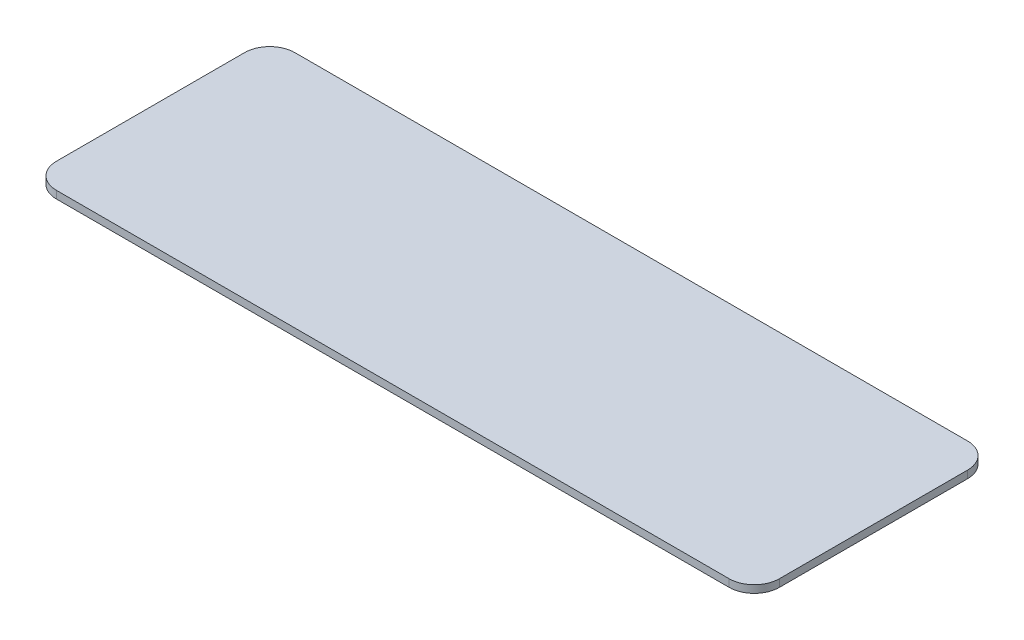
SolidWorks part; units mm, degrees
ref_plane "Front Plane" through (0, 0, 0) normal (0, 0, 1) x (1, 0, 0)
ref_plane "Top Plane" through (0, 0, 0) normal (0, 1, 0) x (1, 0, 0)
ref_plane "Right Plane" through (0, 0, 0) normal (1, 0, 0) x (0, 0, -1)
sketch "Sketch1" plane through (0, 0, 0) normal (0, 1, 0) x (1, 0, 0)
  line L1 (-51.418, 25.835) -> (236.582, 25.835)
  line L2 (-51.418, 25.835) -> (-51.418, -69.165)
  line L3 (-51.418, -69.165) -> (236.582, -69.165)
  line L4 (236.582, 25.835) -> (236.582, -69.165)
  dimension "D1" = 288
  dimension "D2" = 95
extrude "Boss-Extrude1" add sketch "Sketch1" along normal blind 3
sketch "Sketch2" plane through (0, 0, 0) normal (0, -1, 0) x (1, 0, 0)
  line L0 (236.582, -25.835) -> (-51.418, -25.835) construction
  line L1 (-31.418, -25.835) -> (216.582, -25.835)
  line L2 (-31.418, -25.835) -> (-31.418, 49.165)
  line L3 (-31.418, 49.165) -> (216.582, 49.165)
  line L4 (216.582, -25.835) -> (216.582, 49.165)
  line L6 (236.582, 69.165) -> (236.582, -25.835) construction
  dimension "D1" = 248
  dimension "D2" = 75
  dimension "D3" = 20
extrude "Boss-Extrude2" add sketch "Sketch2" along normal blind 6
fillet "Fillet1" radius 10 4 edges at (236.582, 1.5, -25.835) (-51.418, 1.5, -25.835) (236.582, 1.5, 69.165) (-51.418, 1.5, 69.165)
fillet "Fillet2" radius 5 4 edges at (-31.418, -3, 49.165) (216.582, -3, 49.165)
